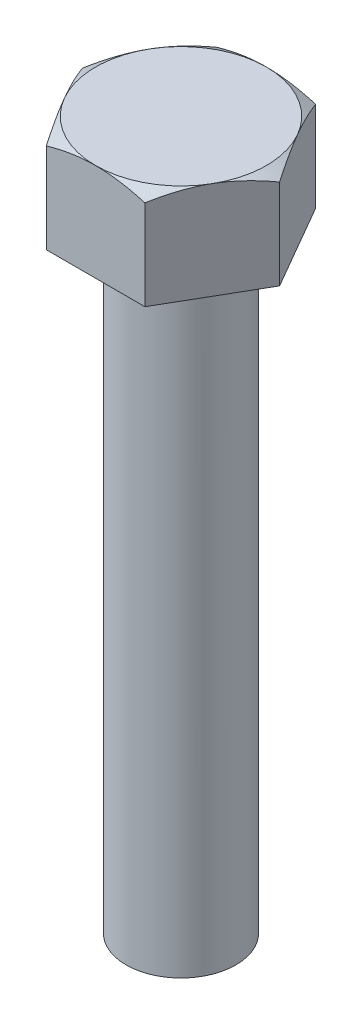
SolidWorks part; units mm, degrees
ref_plane "Front Plane" through (0, 0, 0) normal (0, 0, 1) x (1, 0, 0)
ref_plane "Top Plane" through (0, 0, 0) normal (0, 1, 0) x (1, 0, 0)
ref_plane "Right Plane" through (0, 0, 0) normal (1, 0, 0) x (0, 0, -1)
sketch "Sketch3" plane through (0, 0, 0) normal (0, 1, 0) x (1, 0, 0)
  line L1 (4.0415, 0) -> (2.0207, 3.5)
  line L2 (2.0207, 3.5) -> (-2.0207, 3.5)
  line L3 (-2.0207, 3.5) -> (-4.0415, 0)
  line L4 (-4.0415, 0) -> (-2.0207, -3.5)
  line L5 (-2.0207, -3.5) -> (2.0207, -3.5)
  line L6 (2.0207, -3.5) -> (4.0415, 0)
  circle A0 centre (0, 0) radius 3.5 construction
  dimension "D1" = 7
extrude "Boss-Extrude1" add sketch "Sketch3" against normal blind 4
sketch "Sketch7" plane through (0, 0, 0) normal (0, 1, 0) x (1, 0, 0)
  circle A0 centre (0, 0) radius 3.5
sketch "Sketch8" plane through (0, 0, 0) normal (0, 0, 1) x (1, 0, 0)
  line L0 (3.5, 0) -> (4.0415, 0)
  line L1 (2.0207, 0) -> (4.0415, 0) construction
  line L2 (3.5, 0) -> (-3.5, 0) construction
  line L3 (4.0415, 0) -> (4.0415, -0.3126)
  line L4 (4.0415, -4) -> (4.0415, 0) construction
  line L5 (4.0415, -0.3126) -> (3.5, 0)
  line L6 (0, 2.3281) -> (0, -2.3281) construction
  point P18 (0, 0)
  dimension "D1" = 30
revolve "Cut-Revolve2" cut sketch "Sketch8" angle 360 about L6
sketch "Sketch9" plane through (0, -4, 0) normal (0, -1, 0) x (1, 0, 0)
  circle A0 centre (0, 0) radius 2.25
  dimension "D1" = 4.5
extrude "Boss-Extrude2" add sketch "Sketch9" along normal blind 25
